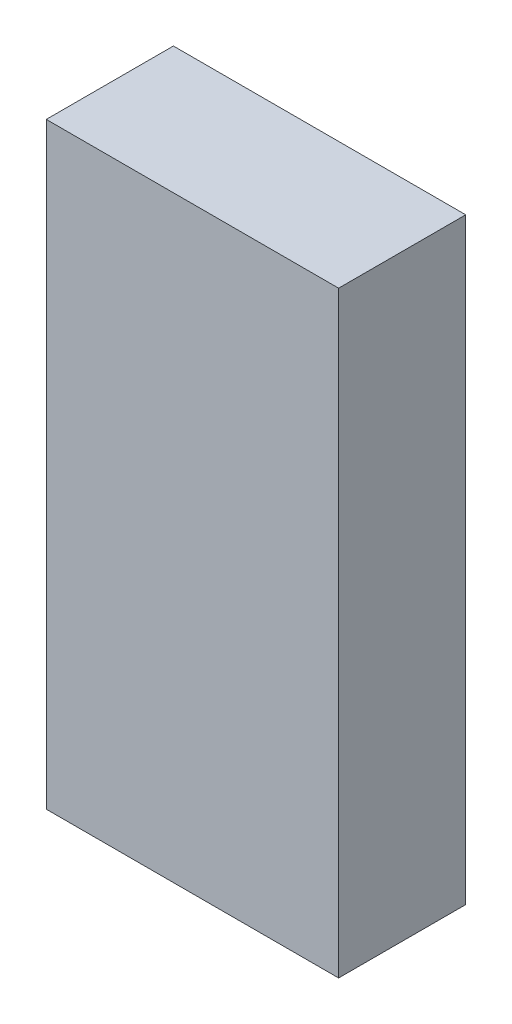
SolidWorks part; units mm, degrees
ref_plane "Front Plane" through (0, 0, 0) normal (0, 0, 1) x (1, 0, 0)
ref_plane "Top Plane" through (0, 0, 0) normal (0, 1, 0) x (1, 0, 0)
ref_plane "Right Plane" through (0, 0, 0) normal (1, 0, 0) x (0, 0, -1)
sketch "Sketch1" plane through (0, 0, 0) normal (0, 0, 1) x (1, 0, 0)
  line L1 (-57.5, 117.5) -> (57.5, 117.5)
  line L2 (-57.5, 117.5) -> (-57.5, -117.5)
  line L3 (-57.5, -117.5) -> (57.5, -117.5)
  line L4 (57.5, 117.5) -> (57.5, -117.5)
  point P0 (0, 0)
  dimension "D1" = 235
  dimension "D2" = 115
extrude "Boss-Extrude1" add sketch "Sketch1" along normal blind 50
